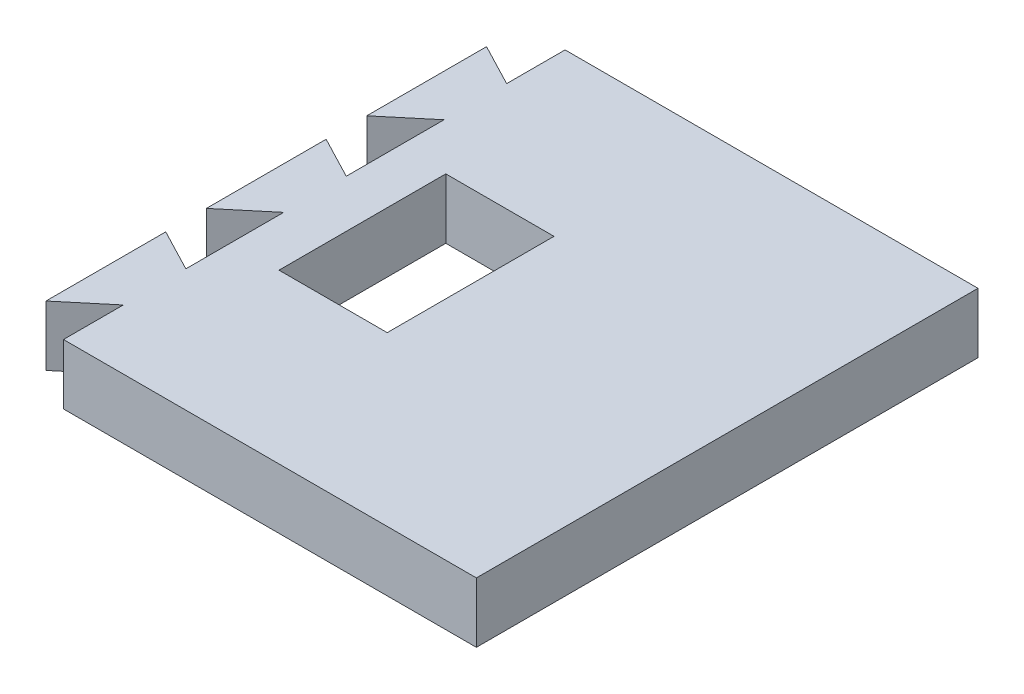
SolidWorks part; units mm, degrees
ref_plane "Front Plane" through (0, 0, 0) normal (0, 0, 1) x (1, 0, 0)
ref_plane "Top Plane" through (0, 0, 0) normal (0, 1, 0) x (1, 0, 0)
ref_plane "Right Plane" through (0, 0, 0) normal (1, 0, 0) x (0, 0, -1)
sketch "Sketch1" plane through (0, 0, 0) normal (0, 1, 0) x (1, 0, 0)
  line L1 (-140, 105) -> (140, 105)
  line L2 (-140, 105) -> (-140, -105)
  line L3 (-140, -105) -> (140, -105)
  line L4 (140, 105) -> (140, -105)
  line L5 (-140, 105) -> (140, -105) construction
  line L6 (-140, -105) -> (140, 105) construction
  point P0 (0, 0)
  dimension "D1" = 280
  dimension "D2" = 210
extrude "Boss-Extrude1" add sketch "Sketch1" along normal blind 15
sketch "Sketch2" plane through (0, 15, 0) normal (0, 1, 0) x (1, 0, 0)
  line L0 (-105, 0) -> (-100, 0) construction
  line L2 (-100, 0) -> (-95, 0) construction
  line L3 (-100, 0) -> (-100, 5) construction
  line L4 (-100, 0) -> (-100, -5) construction
  line L5 (-75, 0) -> (-62.5, 0) construction
  line L6 (-100, -40) -> (-100, -45) construction
  line L7 (-100, 40) -> (-100, 45) construction
  circle A3 centre (-100, 0) radius 5
  circle A4 centre (-100, 45) radius 5
  circle A5 centre (-100, -45) radius 5
  dimension "D3" = 45
  dimension "D4" = 45
  dimension "D2" = 37.5
extrude "Boss-Extrude2" add sketch "Sketch2" along normal blind 50
sketch "Sketch3" plane through (0, 15, 0) normal (0, 1, 0) x (1, 0, 0)
  line L1 (5, 15) -> (-5, 15)
  line L2 (5, 15) -> (5, -15)
  line L3 (5, -15) -> (-5, -15)
  line L4 (-5, 15) -> (-5, -15)
  line L5 (5, 15) -> (-5, -15) construction
  line L6 (5, -15) -> (-5, 15) construction
  point P0 (0, 0)
extrude "Boss-Extrude3" add sketch "Sketch3" along normal up to surface (50 mm away) up to face at (-100, 65, 50)
sketch "Sketch4" plane through (5, 0, 0) normal (1, 0, 0) x (0, 0, -1)
  circle A0 centre (0, 41.2362) radius 13
extrude "Cut-Extrude1" cut sketch "Sketch4" against normal blind 20 contours A0
sketch "Sketch5" plane through (0, 0, 0) normal (0, 1, 0) x (1, 0, 0)
  line L1 (124.0869, 62.5479) -> (-124.0869, 62.5479)
  line L2 (124.0869, 62.5479) -> (124.0869, -62.5479)
  line L3 (124.0869, -62.5479) -> (-124.0869, -62.5479)
  line L4 (-124.0869, 62.5479) -> (-124.0869, -62.5479)
  line L7 (-178.9003, 121.3967) -> (181.5906, 121.3967)
  line L8 (-178.9003, 121.3967) -> (-178.9003, -127.786)
  line L9 (-178.9003, -127.786) -> (181.5906, -127.786)
  line L10 (181.5906, 121.3967) -> (181.5906, -127.786)
  line L11 (-124.0869, 62.5479) -> (124.0869, 62.5479)
  line L13 (-124.0869, 121.3967) -> (181.5906, 121.3967)
  line L14 (181.5906, 62.5479) -> (181.5906, 121.3967)
  line L17 (-124.0869, 121.3967) -> (-178.9003, 121.3967)
  line L18 (-178.9003, 62.5479) -> (-178.9003, 121.3967)
  line L20 (-178.9003, 62.5479) -> (-178.9003, -127.786)
  line L21 (-178.9003, -127.786) -> (-124.0869, -127.786)
  line L22 (-124.0869, 62.5479) -> (-124.0869, -62.5479)
  line L23 (-124.0869, -62.5479) -> (124.0869, -62.5479)
  line L25 (-124.0869, -127.786) -> (181.5906, -127.786)
  line L26 (181.5906, -62.5479) -> (181.5906, -127.786)
  line L28 (124.0869, 62.5479) -> (124.0869, -62.5479)
  line L30 (181.5906, 62.5479) -> (181.5906, -62.5479)
  point P0 (0, 0)
sketch "Sketch6" plane through (0, 0, 0) normal (0, 1, 0) x (1, 0, 0)
extrude "Cut-Extrude5" cut sketch "Sketch5" along normal up to surface (15 mm away) contours L10 L7 L8 L9 L4 L1 L2 L3 up to face at (-100, 15, 50)
sketch "Sketch7" plane through (0, 65, 0) normal (0, 1, 0) x (1, 0, 0)
  circle A0 centre (-100, 45) radius 5
  circle A1 centre (-100, 0) radius 5
  circle A2 centre (-100, -45) radius 5
extrude "Cut-Extrude6" cut sketch "Sketch7" against normal up to surface (65 mm away) up to face at (0, 0, 0)
sketch "Sketch8" plane through (0, 0, 0) normal (0, -1, 0) x (1, 0, 0)
  circle A0 centre (-100, 45) radius 10.1
  circle A1 centre (-100, 0) radius 10.1
  circle A2 centre (-100, -45) radius 10.1
  dimension "D1" = 20.2
  dimension "D2" = 20.2
  dimension "D3" = 20.2
sketch "Sketch9" plane through (0, 15, 0) normal (0, 1, 0) x (1, 0, 0)
  line L0 (-33.7328, 55.5479) -> (-63.0628, 55.5479)
  line L1 (-33.7328, 55.5479) -> (-33.7328, 38.6279)
  line L2 (-33.7328, 38.6279) -> (-63.0628, 38.6279)
  line L3 (-63.0628, 55.5479) -> (-63.0628, 38.6279)
  line L4 (-33.7328, 55.5479) -> (-63.0628, 38.6279) construction
  line L5 (-33.7328, 38.6279) -> (-63.0628, 55.5479) construction
  line L6 (-48.3978, 55.5479) -> (-48.3978, 62.5479) construction
  line L7 (124.0869, 62.5479) -> (-124.0869, 62.5479) construction
  point P0 (-48.3978, 47.0879)
  dimension "D1" = 7
  dimension "D2" = 16.92
  dimension "D3" = 29.33
sketch "Sketch10" plane through (0, 15, 0) normal (0, 1, 0) x (1, 0, 0)
  line L0 (10.618, 13.4516) -> (10.618, -16.4077)
  line L5 (10.618, -56.4077) -> (21.1123, -47.6292)
  line L7 (21.1123, 62.3479) -> (21.1123, 47.9763)
  line L9 (10.618, 53.4516) -> (10.618, 23.5923)
  line L10 (21.1123, -32.0237) -> (10.618, -26.5484)
  line L11 (21.1123, 7.9763) -> (10.618, 13.4516)
  line L12 (10.618, -16.4077) -> (21.1123, -7.6292)
  line L13 (21.1123, 47.9763) -> (10.618, 53.4516)
  line L14 (10.618, 23.5923) -> (21.1123, 32.3708)
  line L15 (10.618, -26.5484) -> (10.618, -56.4077)
  line L20 (21.1123, 32.3708) -> (21.1123, 7.9763)
  line L21 (21.1123, 167.9763) -> (10.618, 173.4516) [skipped]
  line L22 (10.618, 143.5923) -> (21.1123, 152.3708) [skipped]
  line L23 (21.1123, 127.9763) -> (10.618, 133.4516) [skipped]
  line L24 (10.618, 103.5923) -> (21.1123, 112.3708) [skipped]
  line L25 (21.1123, 87.9763) -> (10.618, 93.4516) [skipped]
  line L26 (10.618, 63.5923) -> (21.1123, 72.3708) [skipped]
  line L27 (21.1123, -7.6292) -> (21.1123, -32.0237)
  line L30 (21.1123, -47.6292) -> (21.1123, -62.3479)
  line L40 (21.1123, 62.3479) -> (21.1123, 83.144)
  line L41 (21.1123, 83.144) -> (-140.7043, 77.8495)
  line L42 (-140.7043, 77.8495) -> (-140.7043, -76.0232)
  line L43 (-140.7043, -76.0232) -> (21.1123, -67.0488)
  line L44 (21.1123, -67.0488) -> (21.1123, -62.3479)
  point P16 (0, 0)
  dimension "D2" = 24.3945
  dimension "D3" = 14.3716
  dimension "D4" = 14.7186
  dimension "D5" = 29.8593
  dimension "D1" = 6
sketch "Sketch11" plane through (0, 65, 0) normal (0, 1, 0) x (1, 0, 0)
  line L1 (5.6129, 18.8038) -> (-11.6186, 18.8038)
  line L2 (5.6129, 18.8038) -> (5.6129, -18.5312)
  line L3 (5.6129, -18.5312) -> (-11.6186, -18.5312)
  line L4 (-11.6186, 18.8038) -> (-11.6186, -18.5312)
extrude "Cut-Extrude9" cut sketch "Sketch9" against normal through all
extrude "Cut-Extrude11" cut sketch "Sketch8" against normal blind 10
sketch "Sketch13" plane through (0, 15, 0) normal (0, 1, 0) x (1, 0, 0)
  line L0 (124.0869, 62.5479) -> (-124.0869, 62.5479) construction
  line L1 (0, 0) -> (0, 62.5479) construction
  line L6 (33.0154, 20.8978) -> (33.0154, -20.6978)
  line L9 (-43.0154, -20.6978) -> (-70, -20.6978)
  line L10 (-70, 20.8978) -> (-70, -20.6978)
  line L11 (-70, 20.8978) -> (-43.0154, 20.8978)
  line L12 (-43.0154, 20.8978) -> (-43.0154, -20.6978)
  line L15 (33.0154, -20.6978) -> (60, -20.6978)
  line L16 (60, 20.8978) -> (60, -20.6978)
  line L17 (60, 20.8978) -> (33.0154, 20.8978)
  point P0 (-70, 0.1)
  point P2 (-70, 0.1)
  point P4 (-56.6702, 0)
  dimension "D1" = 26.9846
  dimension "D2" = 41.5955
  dimension "D3" = 60
extrude "Cut-Extrude13" cut sketch "Sketch11" against normal up to surface (50 mm away) up to face at (-48.3978, 15, -47.0879)
sketch "Sketch15" plane through (0, 15, 0) normal (0, 1, 0) x (1, 0, 0)
  line L0 (-100, 0) -> (-75, 0) construction
  line L2 (-70, -25) -> (-80, -25)
  line L3 (-70, -25) -> (-70, 25)
  line L4 (-70, 25) -> (-80, 25)
  line L5 (-80, -25) -> (-80, 25)
  line L6 (-70, -25) -> (-80, 25) construction
  line L7 (-70, 25) -> (-80, -25) construction
  dimension "D1" = 25
  dimension "D2" = 10
  dimension "D3" = 50
extrude "Cut-Extrude14" cut sketch "Sketch15" against normal blind 5
extrude "Cut-Extrude17" cut sketch "Sketch13" against normal through all
extrude "Cut-Extrude18" cut sketch "Sketch10" against normal through all
